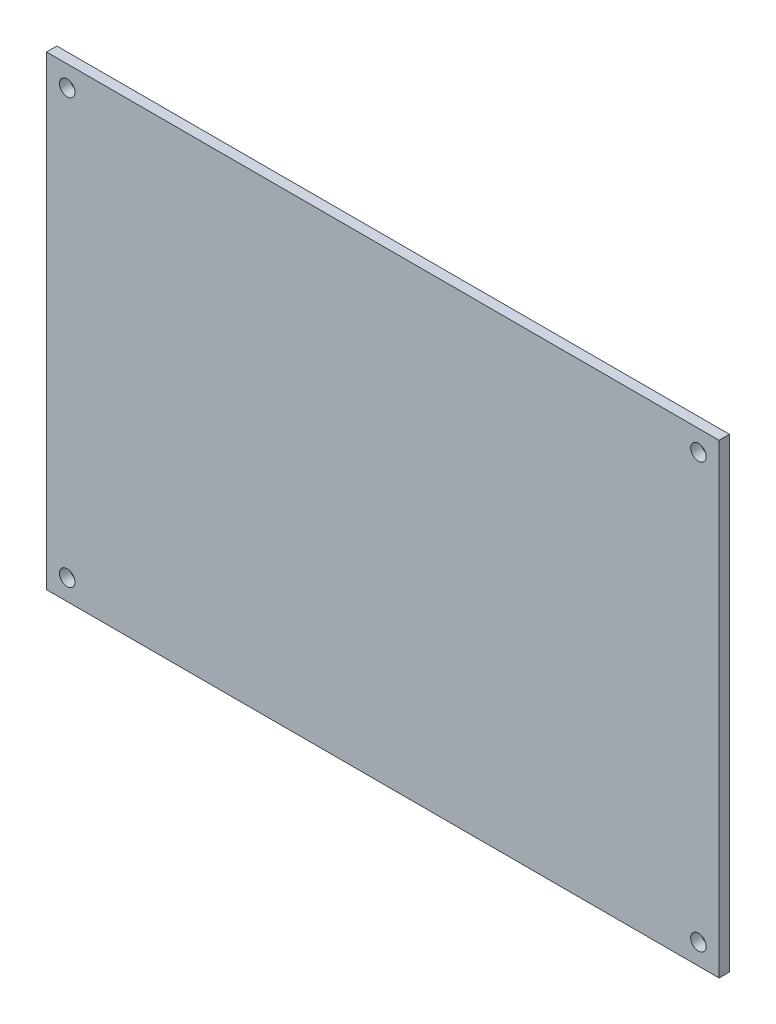
SolidWorks part; units mm, degrees
ref_plane "Front Plane" through (0, 0, 0) normal (0, 0, 1) x (1, 0, 0)
ref_plane "Top Plane" through (0, 0, 0) normal (0, 1, 0) x (1, 0, 0)
ref_plane "Right Plane" through (0, 0, 0) normal (1, 0, 0) x (0, 0, -1)
sketch "Sketch1" plane through (0, 0, 0) normal (0, 0, 1) x (1, 0, 0)
  line L1 (0, 0) -> (165.1, 0)
  line L2 (0, 0) -> (0, 114.3)
  line L3 (0, 114.3) -> (165.1, 114.3)
  line L4 (165.1, 0) -> (165.1, 114.3)
  circle A0 centre (5.08, 109.22) radius 1.905
  circle A1 centre (160.02, 109.22) radius 1.905
  circle A2 centre (160.02, 5.08) radius 1.905
  circle A3 centre (5.08, 5.08) radius 1.905
  dimension "D3" = 5.08
  dimension "D4" = 5.08
  dimension "D5" = 5.08
  dimension "D6" = 5.08
  dimension "D8" = 5.08
  dimension "D9" = 5.08
  dimension "D10" = 5.08
  dimension "D11" = 3.81
  dimension "D1" = 165.1
  dimension "D2" = 114.3
  dimension "D7" = 5.08
extrude "Extrude1" add sketch "Sketch1" along normal blind 2.54
